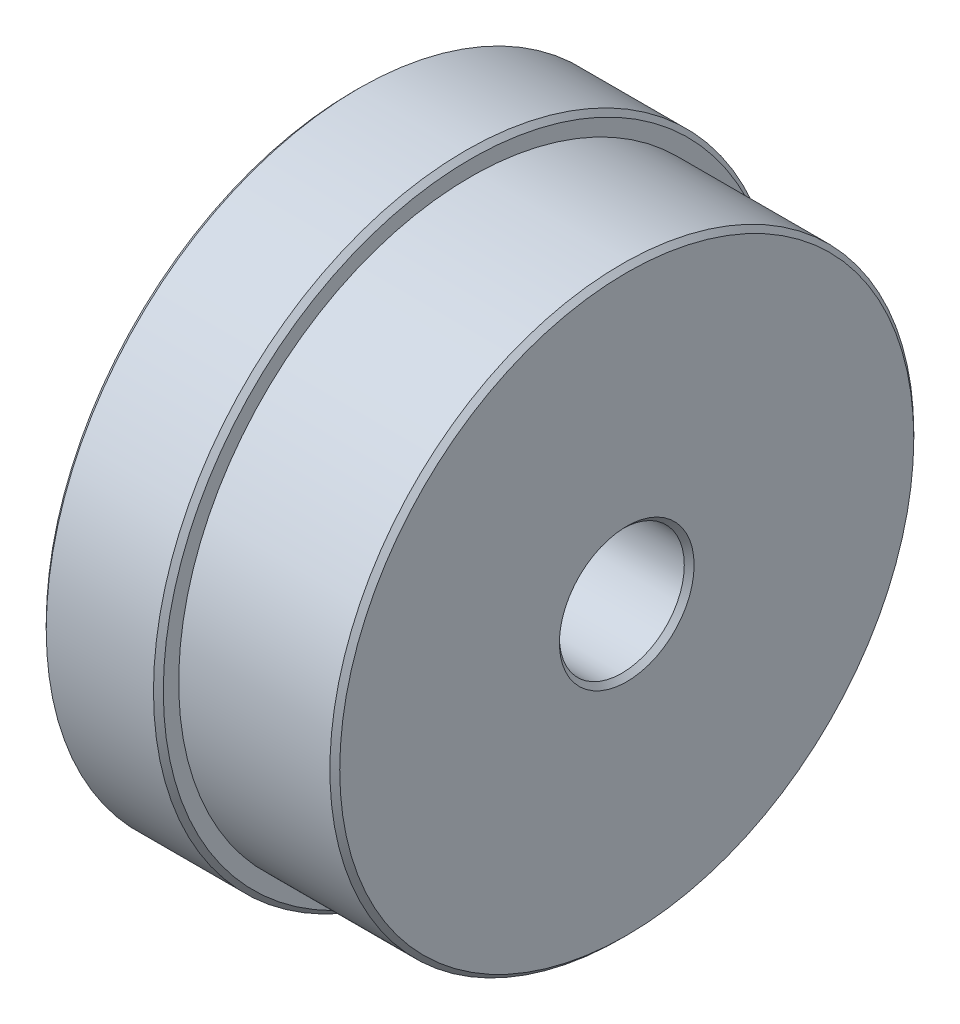
SolidWorks part; units mm, degrees
material "Nylon 101"
ref_plane "Front Plane" through (0, 0, 0) normal (0, 0, 1) x (1, 0, 0)
ref_plane "Top Plane" through (0, 0, 0) normal (0, 1, 0) x (1, 0, 0)
ref_plane "Right Plane" through (0, 0, 0) normal (1, 0, 0) x (0, 0, -1)
sketch "Sketch1" plane through (0, 0, 0) normal (1, 0, 0) x (0, 0, -1)
  circle A0 centre (0, 0) radius 23.749
  dimension "D1" = 47.498
extrude "Boss-Extrude1" add sketch "Sketch1" along normal blind 12.7
sketch "Sketch2" plane through (0, 0, 0) normal (-1, 0, 0) x (0, 0, 1)
  circle A0 centre (0, 0) radius 25.4
  dimension "D1" = 50.8
extrude "Boss-Extrude2" add sketch "Sketch2" along normal blind 9.525
sketch "Sketch3" plane through (-9.525, 0, 0) normal (-1, 0, 0) x (0, 0, 1)
  circle A0 centre (0, 0) radius 11.1125
  dimension "D1" = 22.225
extrude "Cut-Extrude1" cut sketch "Sketch3" against normal blind 7.112
sketch "Sketch4" plane through (-2.413, 0, 0) normal (-1, 0, 0) x (0, 0, 1)
  circle A0 centre (0, 0) radius 7.2746
  dimension "D1" = 14.5492
extrude "Cut-Extrude2" cut sketch "Sketch4" against normal blind 0.2
sketch "Sketch5" plane through (-2.213, 0, 0) normal (-1, 0, 0) x (0, 0, 1)
  circle A0 centre (0, 0) radius 5.08
  dimension "D1" = 10.16
extrude "Cut-Extrude3" cut sketch "Sketch5" against normal through all
chamfer "Chamfer1" distance 0.4 angle 45 5 edges at (12.7, 0, -23.749) (12.7, 0, 5.08) (-9.525, 0, 25.4) (-9.525, 0, 11.1125) (0, 0, 25.4)
